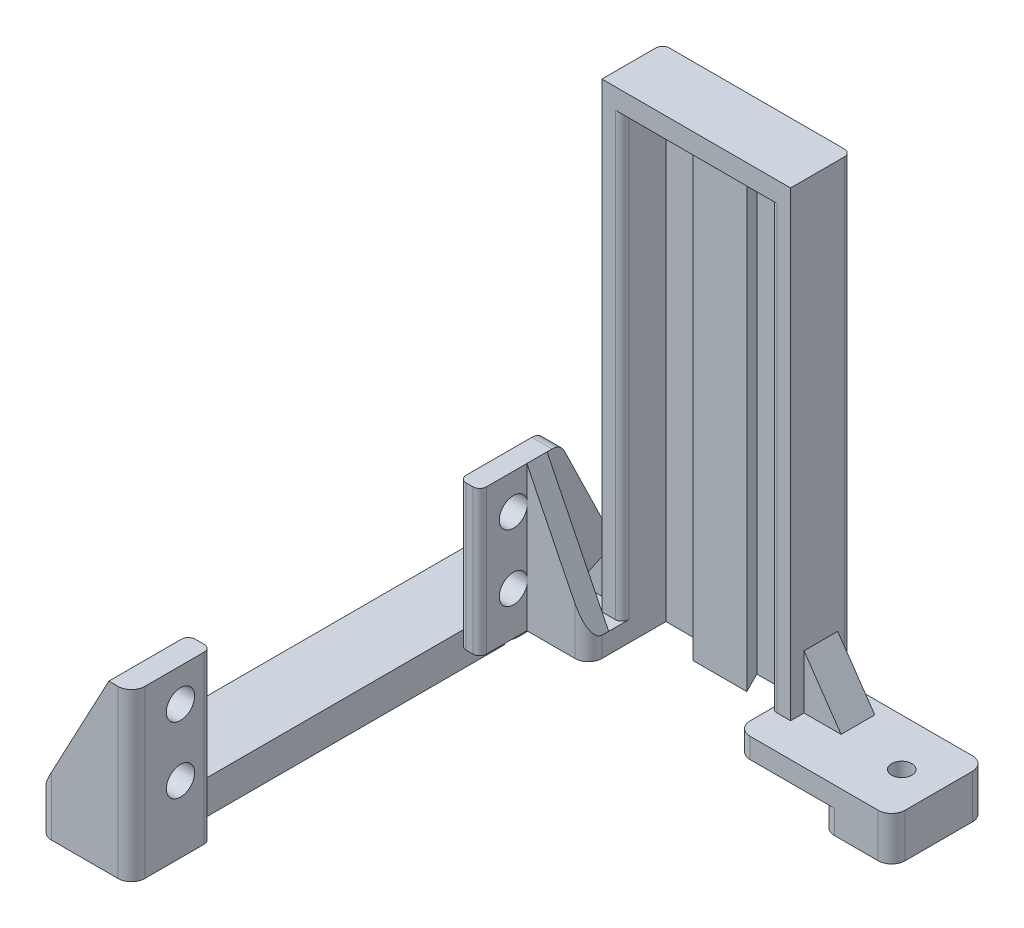
SolidWorks part; units mm, degrees
ref_plane "前视基准面" through (0, 0, 0) normal (0, 0, 1) x (1, 0, 0)
ref_plane "上视基准面" through (0, 0, 0) normal (0, 1, 0) x (1, 0, 0)
ref_plane "右视基准面" through (0, 0, 0) normal (1, 0, 0) x (0, 0, -1)
other "Configuration Table"
sketch "草图1" plane through (0, 0, 0) normal (0, 1, 0) x (1, 0, 0)
  line L1 (-14, -7) -> (14, -7)
  line L2 (-14, -7) -> (-14, 7)
  line L3 (-14, 7) -> (14, 7)
  line L4 (14, -7) -> (14, 7)
  line L5 (-14, -7) -> (14, 7) construction
  line L6 (-14, 7) -> (14, -7) construction
  line L7 (-11, -4) -> (11, -4)
  line L8 (-11, -4) -> (-11, 4)
  line L9 (-11, 4) -> (11, 4)
  line L10 (11, -4) -> (11, 4)
  line L11 (-11, -4) -> (11, 4) construction
  line L12 (-11, 4) -> (11, -4) construction
  point P0 (0, 0)
  point P6 (0, 0)
  point P11 (0, 4)
  dimension "D1" = 28
  dimension "D2" = 22
  dimension "D3" = 14
  dimension "D4" = 3
extrude "凸台-拉伸1" add sketch "草图1" along normal blind 75
sketch "草图2" plane through (0, 75, 0) normal (0, 1, 0) x (1, 0, 0)
  line L1 (-11, 4) -> (11, 4)
  line L2 (-11, 4) -> (-11, -4)
  line L3 (-11, -4) -> (11, -4)
  line L4 (11, 4) -> (11, -4)
extrude "凸台-拉伸2" add sketch "草图2" against normal blind 3
sketch "草图3" plane through (0, 0, 0) normal (0, -1, 0) x (1, 0, 0)
  line L0 (-14, 7) -> (14, 7) construction
  line L1 (-11, 7) -> (11, 7)
  line L2 (-11, 7) -> (-11, -4)
  line L3 (-11, -4) -> (11, -4)
  line L4 (11, 7) -> (11, -4)
  line L7 (11, -4) -> (-11, -4) construction
  point P7 (0, 7)
  point P8 (-9.2889, 7)
  point P9 (-9.2889, 7)
  dimension "D1" = 22
extrude "切除-拉伸1" cut sketch "草图3" against normal blind 72
sketch "草图4" plane through (0, 0, 0) normal (0, -1, 0) x (1, 0, 0)
  line L0 (11, 7) -> (-11, 7) construction
  line L1 (-34, 7) -> (34, 7)
  line L2 (-34, 7) -> (-34, -7)
  line L3 (-34, -7) -> (34, -7)
  line L4 (34, 7) -> (34, -7)
  line L5 (14, -7) -> (-14, -7) construction
  line L6 (-14, -7) -> (-14, 7) construction
  point P4 (0, 7)
  point P5 (0, -7)
  point P8 (0, -7)
  point P11 (0, 7)
  line M5 (-14, 7) -> (-14, -7)
  line M7 (14, -7) -> (14, 7)
  dimension "D1" = 20
extrude "凸台-拉伸3" add sketch "草图4" against normal blind 6.5 contours L2 L3 L1 M5 | L4 L1 L3 M7
sketch "草图5" plane through (0, 0, 0) normal (0, -1, 0) x (1, 0, 0)
  line L4 (-34, 7) -> (-11, 7) construction
  circle A0 centre (-28.5, 0) radius 1.5
  circle A1 centre (28.5, 0) radius 1.5
  dimension "D1" = 3
  dimension "D2" = 3
  dimension "D3" = 57
  dimension "D4" = 28.5
  dimension "D5" = 7
extrude "切除-拉伸2" cut sketch "草图5" against normal through all
fillet "圆角1" radius 2 3 edges at (34, 3.25, 7) (34, 3.25, -7) (-34, 3.25, -7)
sketch "草图7" plane through (0, 0, 0) normal (0, -1, 0) x (1, 0, 0)
  line L0 (-2.5, -4.5) -> (2.5, -4.5)
  line L2 (11, -4) -> (-11, -4) construction
  line L3 (2.5, -4.5) -> (4, -1.5)
  line L4 (4, -1.5) -> (-4, -1.5)
  line L5 (-4, -1.5) -> (-2.5, -4.5)
  line L6 (0, -28.9) -> (0, 52.5) construction
  point P9 (0, -4.5)
  dimension "D1" = 8
  dimension "D2" = 5
  dimension "D3" = 3
  dimension "D4" = 0.5
extrude "凸台-拉伸5" add sketch "草图7" against normal up to next
sketch "草图9" plane through (0, 75, 0) normal (0, 1, 0) x (1, 0, 0)
  line L0 (-14, 7) -> (-14, -7) construction
  line L1 (14, -7) -> (-14, -7)
  line L2 (14, -7) -> (14, -2)
  line L3 (14, -2) -> (-14, -2)
  line L4 (-14, -7) -> (-14, -2)
  dimension "D1" = 5
extrude "切除-拉伸3" cut sketch "草图9" against normal offset from surface (68.5 mm away) 6.5 up to face at (-28.5, 0, -1.5)
fillet "圆角3" radius 1 4 edges at (-14, 40.75, -7) (14, 40.75, -7) (-11, 39.25, 2) (11, 39.25, 2)
ref_plane "基准面1" through (0, 37.5, 0) normal (0, 1, 0) x (1, 0, 0)
ref_plane "基准面2" through (0, 0, -2.5) normal (0, 0, -1) x (-1, 0, 0)
sketch "草图10" plane through (0, 0, -2.5) normal (0, 0, -1) x (-1, 0, 0)
  line L0 (-14, 6.5) -> (-19.5, 6.5)
  line L1 (-13, 6.5) -> (-32, 6.5) construction
  line L2 (-19.5, 6.5) -> (-14, 14.5)
  line L3 (-14, 6.5) -> (-14, 75) construction
  line L4 (-14, 14.5) -> (-14, 6.5)
  dimension "D1" = 5.5
  dimension "D2" = 8
extrude "凸台-拉伸6" add sketch "草图10" along normal mid plane 5
mirror "镜向2" about plane through (0, 0, 0) normal (1, 0, 0) of "凸台-拉伸6"
ref_plane "基准面3" through (-20.15, 0, 0) normal (-1, 0, 0) x (0, 0, 1)
sketch "草图11" plane through (-20.15, 0, 0) normal (-1, 0, 0) x (0, 0, 1)
  line L0 (2, 6.5) -> (2, 75) construction
  line L1 (2, 0) -> (14, 0)
  line L2 (2, 0) -> (2, 25)
  line L3 (2, 25) -> (14, 25)
  line L4 (14, 0) -> (14, 25)
  line L10 (5, 0) -> (-5, 0) construction
  circle A0 centre (8.9889, 19.775) radius 2.1
  circle A1 centre (8.9889, 9.925) radius 2.1
  point P6 (8.9889, 9.925)
  dimension "D3" = 4.2
  dimension "D4" = 4.2
  dimension "D1" = 12
  dimension "D2" = 25
  dimension "D5" = 9.85
extrude "凸台-拉伸7" add sketch "草图11" along normal blind 3
ref_plane "基准面4" through (-21.65, 0, 0) normal (-1, 0, 0) x (0, 0, 1)
sketch "草图14" plane through (-23.15, 0, 0) normal (-1, 0, 0) x (0, 0, 1)
  line L0 (2, 25) -> (-7, 6.5)
  line L1 (-7, 6.5) -> (2, 6.5)
  line L2 (2, 6.5) -> (2, 25)
extrude "凸台-拉伸9" add sketch "草图14" against normal blind 3
sketch "草图12" plane through (0, 0, 7) normal (0, 0, 1) x (1, 0, 0)
  line L0 (-20.15, 6.5) -> (-20.15, 25)
  line L3 (-20.15, 25) -> (-11, 6.5)
  line L5 (-11, 6.5) -> (-20.15, 6.5)
  line L6 (-20.15, 6.5) -> (-11, 6.5) construction
extrude "凸台-拉伸8" add sketch "草图12" against normal blind 3
fillet "圆角11" [suppressed] radius 2
sketch "草图15" [suppressed] plane through (-20.15, 0, 0) normal (1, 0, 0) x (0, 0, -1)
  line L0 (-17, 2) -> (-17, 23) construction
  line L1 (-9, 0) -> (-17, 0)
  line L2 (-9, 0) -> (-9, 4.8)
  line L3 (-9, 4.8) -> (-17, 4.8)
  line L4 (-17, 0) -> (-17, 4.8)
  dimension "D1" = 4.8
sketch "草图16" plane through (0, 0, 0) normal (0, -1, 0) x (1, 0, 0)
  line L1 (-23.5, -7) -> (23.5, -7)
  line L2 (-23.5, -7) -> (-23.5, 17)
  line L3 (-23.5, 17) -> (23.5, 17)
  line L4 (23.5, -7) -> (23.5, 17)
  line L5 (32, -7) -> (-32, -7) construction
  dimension "D1" = 47
  dimension "D2" = 24
  dimension "D3" = 23.5
extrude "切除-拉伸4" cut sketch "草图16" against normal blind 3.5
fillet "圆角12" radius 2 6 edges at (-11, 5, 7) (11, 5, 7) (23.5, 1.75, 7) (23.5, 1.75, -7) (-23.5, 1.75, -7) (-23.5, 1.75, 7)
fillet "圆角14" radius 2 1 edges at (-21.65, 25, 2)
sketch "草图17" plane through (0, 0, 7) normal (0, 0, 1) x (1, 0, 0)
  line L0 (-41.45, 5) -> (-20.65, 5) construction
  line L1 (-23.5, 0) -> (-34, 0)
  line L2 (-23.5, 0) -> (-23.5, 5)
  line L3 (-23.5, 5) -> (-34, 5)
  line L4 (-34, 0) -> (-34, 5)
  line L6 (-34, 6.5) -> (-34, 0) construction
extrude "凸台-拉伸10" add sketch "草图17" along normal offset from surface (58.7 mm away) 5
sketch "草图18" plane through (-23.5, 0, 0) normal (1, 0, 0) x (0, 0, -1)
  line L1 (-53.9, 24.7) -> (-65.7, 24.7)
  line L2 (-53.9, 24.7) -> (-53.9, 0)
  line L3 (-53.9, 0) -> (-65.7, 0)
  line L4 (-65.7, 24.7) -> (-65.7, 0)
  line L5 (-65.7, 5) -> (-65.7, 0) construction
  line L6 (-53.35, 24.7) -> (-59.7, 24.7) construction
  line L7 (-53.65, 5.3) -> (-53.65, 24.4) construction
  dimension "D1" = 0.25
extrude "凸台-拉伸11" add sketch "草图18" along normal up to surface (3.35 mm away)
sketch "草图19" plane through (-20.15, 0, 0) normal (1, 0, 0) x (0, 0, -1)
  circle A0 centre (-58.4111, 9.925) radius 2.1
  circle A1 centre (-58.4111, 19.775) radius 2.1
extrude "切除-拉伸5" cut sketch "草图19" against normal up to next
sketch "草图20" plane through (0, 5, 0) normal (0, 1, 0) x (1, 0, 0)
  line L0 (-34, -65.7) -> (-34, -7) construction
  line L1 (-34, -65.7) -> (-23.5, -65.7) construction
  circle A0 centre (-30, -59.7) radius 1.6
  dimension "D1" = 3.2
  dimension "D2" = 4
  dimension "D3" = 6
extrude "切除-拉伸6" cut sketch "草图20" against normal up to next
sketch "草图21" plane through (0, 0, 7) normal (0, 0, 1) x (1, 0, 0)
  line L1 (-34, 6.5) -> (-23.15, 6.5) construction
  line L2 (-23.15, 6.5) -> (-34, 6.5)
  line L3 (-23.15, 6.5) -> (-23.15, 5)
  line L4 (-23.15, 5) -> (-34, 5)
  line L5 (-34, 6.5) -> (-34, 5)
  line L6 (-23.15, 6.5) -> (-23.15, 3.5) construction
extrude "切除-拉伸7" cut sketch "草图21" against normal up to next
sketch "草图22" plane through (0, 0, 65.7) normal (0, 0, 1) x (1, 0, 0)
  line L0 (-23.5, 5) -> (-34, 5)
  line L1 (-34, 5) -> (-23.5, 24.7)
  line L2 (-23.5, 24.7) -> (-23.5, 5)
extrude "凸台-拉伸12" add sketch "草图22" against normal blind 2
fillet "圆角15" radius 2 2 edges at (-34, 2.5, 65.7) (-20.15, 12.35, 65.7)
fillet "圆角16" radius 1 4 edges at (-23.5, 14.85, 53.9) (-20.15, 12.35, 53.9) (-20.15, 14.25, 14) (-23.15, 14.25, 14)
sketch "草图23" plane through (0, 3.5, 0) normal (0, -1, 0) x (1, 0, 0)
  line L0 (-11, -4) -> (-11, -4.5)
  line L1 (-11, -4.5) -> (-2.5, -4.5)
  line L2 (-2.5, -4.5) -> (-2.75, -4)
  line L3 (-2.75, -4) -> (-11, -4)
  line L4 (11, -4) -> (11, -4.5)
  line L5 (11, -4.5) -> (2.5, -4.5)
  line L6 (2.5, -4.5) -> (2.75, -4)
  line L7 (2.75, -4) -> (11, -4)
  line L8 (-4, -1.5) -> (-2.75, -4) construction
  line L9 (2.75, -4) -> (4, -1.5) construction
  dimension "D1" = 0.5
extrude "切除-拉伸8" cut sketch "草图23" against normal up to surface (68.5 mm away) up to face at (0, 72, -1.2586)
